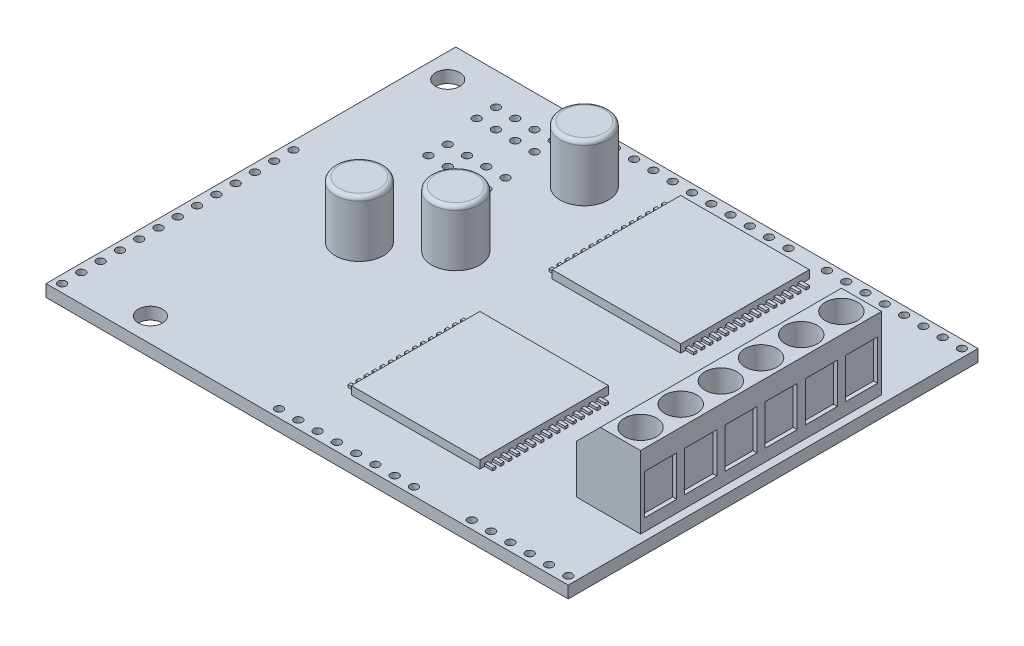
SolidWorks part; units mm, degrees
ref_plane "Спереди" through (0, 0, 0) normal (0, 0, 1) x (1, 0, 0)
ref_plane "Сверху" through (0, 0, 0) normal (0, 1, 0) x (1, 0, 0)
ref_plane "Справа" through (0, 0, 0) normal (1, 0, 0) x (0, 0, -1)
sketch "Эскиз1" plane through (0, 0, 0) normal (0, 1, 0) x (1, 0, 0)
  line L1 (-32.5, 25.5) -> (32.5, 25.5)
  line L2 (-32.5, 25.5) -> (-32.5, -25.5)
  line L3 (-32.5, -25.5) -> (32.5, -25.5)
  line L4 (32.5, 25.5) -> (32.5, -25.5)
  dimension "D1" = 65
  dimension "D2" = 51
  dimension "D3" = 32.5
  dimension "D4" = 25.5
extrude "Бобышка-Вытянуть1" add sketch "Эскиз1" along normal blind 1.5
sketch "Эскиз2" plane through (0, 1.5, 0) normal (0, 1, 0) x (1, 0, 0)
  line L0 (32.5, -25.5) -> (32.5, 25.5) construction
  line L1 (-1.5, 22.5) -> (14.5, 22.5)
  line L2 (-1.5, 22.5) -> (-1.5, 6.5)
  line L3 (-1.5, 6.5) -> (14.5, 6.5)
  line L4 (14.5, 22.5) -> (14.5, 6.5)
  line L5 (32.5, 25.5) -> (-32.5, 25.5) construction
  line L6 (-1.5, -2.5) -> (14.5, -2.5)
  line L7 (-1.5, -2.5) -> (-1.5, -18.5)
  line L8 (-1.5, -18.5) -> (14.5, -18.5)
  line L9 (14.5, -2.5) -> (14.5, -18.5)
  dimension "D1" = 16
  dimension "D2" = 16
  dimension "D3" = 18
  dimension "D4" = 3
  dimension "D5" = 2
extrude "Бобышка-Вытянуть2" add sketch "Эскиз2" along normal blind 1
sketch "Эскиз3" plane through (0, 1.5, 0) normal (0, 1, 0) x (1, 0, 0)
  line L0 (14.5, 6.5) -> (14.5, 22.5) construction
  line L1 (14.5, 21.5) -> (15.5, 21.5)
  line L2 (14.5, 21.5) -> (14.5, 21.1)
  line L3 (14.5, 21.1) -> (15.5, 21.1)
  line L4 (15.5, 21.5) -> (15.5, 21.1)
  line L5 (14.5, 22.5) -> (-1.5, 22.5) construction
  line L6 (14.5, 20.5) -> (15.5, 20.5)
  line L7 (14.5, 20.5) -> (14.5, 20.1)
  line L8 (14.5, 20.1) -> (15.5, 20.1)
  line L9 (15.5, 20.5) -> (15.5, 20.1)
  line L10 (14.5, 19.5) -> (15.5, 19.5)
  line L11 (14.5, 19.5) -> (14.5, 19.1)
  line L12 (14.5, 19.1) -> (15.5, 19.1)
  line L13 (15.5, 19.5) -> (15.5, 19.1)
  line L14 (14.5, 18.5) -> (15.5, 18.5)
  line L15 (14.5, 18.5) -> (14.5, 18.1)
  line L16 (14.5, 18.1) -> (15.5, 18.1)
  line L17 (15.5, 18.5) -> (15.5, 18.1)
  line L18 (14.5, 17.5) -> (15.5, 17.5)
  line L19 (14.5, 17.5) -> (14.5, 17.1)
  line L20 (14.5, 17.1) -> (15.5, 17.1)
  line L21 (15.5, 17.5) -> (15.5, 17.1)
  line L22 (14.5, 16.5) -> (15.5, 16.5)
  line L23 (14.5, 16.5) -> (14.5, 16.1)
  line L24 (14.5, 16.1) -> (15.5, 16.1)
  line L25 (15.5, 16.5) -> (15.5, 16.1)
  line L26 (14.5, 15.5) -> (15.5, 15.5)
  line L27 (14.5, 15.5) -> (14.5, 15.1)
  line L28 (14.5, 15.1) -> (15.5, 15.1)
  line L29 (15.5, 15.5) -> (15.5, 15.1)
  line L30 (14.5, 14.5) -> (15.5, 14.5)
  line L31 (14.5, 14.5) -> (14.5, 14.1)
  line L32 (14.5, 14.1) -> (15.5, 14.1)
  line L33 (15.5, 14.5) -> (15.5, 14.1)
  line L34 (14.5, 13.5) -> (15.5, 13.5)
  line L35 (14.5, 13.5) -> (14.5, 13.1)
  line L36 (14.5, 13.1) -> (15.5, 13.1)
  line L37 (15.5, 13.5) -> (15.5, 13.1)
  line L38 (14.5, 12.5) -> (15.5, 12.5)
  line L39 (14.5, 12.5) -> (14.5, 12.1)
  line L40 (14.5, 12.1) -> (15.5, 12.1)
  line L41 (15.5, 12.5) -> (15.5, 12.1)
  line L42 (14.5, 11.5) -> (15.5, 11.5)
  line L43 (14.5, 11.5) -> (14.5, 11.1)
  line L44 (14.5, 11.1) -> (15.5, 11.1)
  line L45 (15.5, 11.5) -> (15.5, 11.1)
  line L46 (14.5, 10.5) -> (15.5, 10.5)
  line L47 (14.5, 10.5) -> (14.5, 10.1)
  line L48 (14.5, 10.1) -> (15.5, 10.1)
  line L49 (15.5, 10.5) -> (15.5, 10.1)
  line L50 (14.5, 9.5) -> (15.5, 9.5)
  line L51 (14.5, 9.5) -> (14.5, 9.1)
  line L52 (14.5, 9.1) -> (15.5, 9.1)
  line L53 (15.5, 9.5) -> (15.5, 9.1)
  line L54 (14.5, 8.5) -> (15.5, 8.5)
  line L55 (14.5, 8.5) -> (14.5, 8.1)
  line L56 (14.5, 8.1) -> (15.5, 8.1)
  line L57 (15.5, 8.5) -> (15.5, 8.1)
  line L58 (14.5, 7.5) -> (15.5, 7.5)
  line L59 (14.5, 7.5) -> (14.5, 7.1)
  line L60 (14.5, 7.1) -> (15.5, 7.1)
  line L61 (15.5, 7.5) -> (15.5, 7.1)
  line L62 (6.5, 54.7714) -> (6.5, -83.906) construction
  line L63 (-2.5, 7.5) -> (-2.5, 7.1)
  line L64 (-1.5, 7.1) -> (-2.5, 7.1)
  line L65 (-1.5, 7.5) -> (-1.5, 7.1)
  line L66 (-1.5, 7.5) -> (-2.5, 7.5)
  line L67 (-2.5, 8.5) -> (-2.5, 8.1)
  line L68 (-1.5, 8.1) -> (-2.5, 8.1)
  line L69 (-1.5, 8.5) -> (-1.5, 8.1)
  line L70 (-1.5, 8.5) -> (-2.5, 8.5)
  line L71 (-2.5, 9.5) -> (-2.5, 9.1)
  line L72 (-1.5, 9.1) -> (-2.5, 9.1)
  line L73 (-1.5, 9.5) -> (-1.5, 9.1)
  line L74 (-1.5, 9.5) -> (-2.5, 9.5)
  line L75 (-2.5, 10.5) -> (-2.5, 10.1)
  line L76 (-1.5, 10.1) -> (-2.5, 10.1)
  line L77 (-1.5, 10.5) -> (-1.5, 10.1)
  line L78 (-1.5, 10.5) -> (-2.5, 10.5)
  line L79 (-2.5, 11.5) -> (-2.5, 11.1)
  line L80 (-1.5, 11.1) -> (-2.5, 11.1)
  line L81 (-1.5, 11.5) -> (-1.5, 11.1)
  line L82 (-1.5, 11.5) -> (-2.5, 11.5)
  line L83 (-2.5, 12.5) -> (-2.5, 12.1)
  line L84 (-1.5, 12.1) -> (-2.5, 12.1)
  line L85 (-1.5, 12.5) -> (-1.5, 12.1)
  line L86 (-1.5, 12.5) -> (-2.5, 12.5)
  line L87 (-2.5, 13.5) -> (-2.5, 13.1)
  line L88 (-1.5, 13.1) -> (-2.5, 13.1)
  line L89 (-1.5, 13.5) -> (-1.5, 13.1)
  line L90 (-1.5, 13.5) -> (-2.5, 13.5)
  line L91 (-2.5, 14.5) -> (-2.5, 14.1)
  line L92 (-1.5, 14.1) -> (-2.5, 14.1)
  line L93 (-1.5, 14.5) -> (-1.5, 14.1)
  line L94 (-1.5, 14.5) -> (-2.5, 14.5)
  line L95 (-2.5, 15.5) -> (-2.5, 15.1)
  line L96 (-1.5, 15.1) -> (-2.5, 15.1)
  line L97 (-1.5, 15.5) -> (-1.5, 15.1)
  line L98 (-1.5, 15.5) -> (-2.5, 15.5)
  line L99 (-2.5, 16.5) -> (-2.5, 16.1)
  line L100 (-1.5, 16.1) -> (-2.5, 16.1)
  line L101 (-1.5, 16.5) -> (-1.5, 16.1)
  line L102 (-1.5, 16.5) -> (-2.5, 16.5)
  line L103 (-2.5, 17.5) -> (-2.5, 17.1)
  line L104 (-1.5, 17.1) -> (-2.5, 17.1)
  line L105 (-1.5, 17.5) -> (-1.5, 17.1)
  line L106 (-1.5, 17.5) -> (-2.5, 17.5)
  line L107 (-2.5, 18.5) -> (-2.5, 18.1)
  line L108 (-1.5, 18.1) -> (-2.5, 18.1)
  line L109 (-1.5, 18.5) -> (-1.5, 18.1)
  line L110 (-1.5, 18.5) -> (-2.5, 18.5)
  line L111 (-2.5, 19.5) -> (-2.5, 19.1)
  line L112 (-1.5, 19.1) -> (-2.5, 19.1)
  line L113 (-1.5, 19.5) -> (-1.5, 19.1)
  line L114 (-1.5, 19.5) -> (-2.5, 19.5)
  line L115 (-2.5, 20.5) -> (-2.5, 20.1)
  line L116 (-1.5, 20.1) -> (-2.5, 20.1)
  line L117 (-1.5, 20.5) -> (-1.5, 20.1)
  line L118 (-1.5, 20.5) -> (-2.5, 20.5)
  line L119 (-2.5, 21.5) -> (-2.5, 21.1)
  line L120 (-1.5, 21.1) -> (-2.5, 21.1)
  line L121 (-1.5, 21.5) -> (-1.5, 21.1)
  line L122 (-1.5, 21.5) -> (-2.5, 21.5)
  line L123 (14.5, -3.5) -> (15.5, -3.5)
  line L124 (14.5, -3.5) -> (14.5, -3.9)
  line L125 (14.5, -3.9) -> (15.5, -3.9)
  line L126 (15.5, -3.5) -> (15.5, -3.9)
  line L127 (14.5, -4.5) -> (15.5, -4.5)
  line L128 (14.5, -4.5) -> (14.5, -4.9)
  line L129 (14.5, -4.9) -> (15.5, -4.9)
  line L130 (15.5, -4.5) -> (15.5, -4.9)
  line L131 (14.5, -5.5) -> (15.5, -5.5)
  line L132 (14.5, -5.5) -> (14.5, -5.9)
  line L133 (14.5, -5.9) -> (15.5, -5.9)
  line L134 (15.5, -5.5) -> (15.5, -5.9)
  line L135 (14.5, -6.5) -> (15.5, -6.5)
  line L136 (14.5, -6.5) -> (14.5, -6.9)
  line L137 (14.5, -6.9) -> (15.5, -6.9)
  line L138 (15.5, -6.5) -> (15.5, -6.9)
  line L139 (14.5, -7.5) -> (15.5, -7.5)
  line L140 (14.5, -7.5) -> (14.5, -7.9)
  line L141 (14.5, -7.9) -> (15.5, -7.9)
  line L142 (15.5, -7.5) -> (15.5, -7.9)
  line L143 (14.5, -8.5) -> (15.5, -8.5)
  line L144 (14.5, -8.5) -> (14.5, -8.9)
  line L145 (14.5, -8.9) -> (15.5, -8.9)
  line L146 (15.5, -8.5) -> (15.5, -8.9)
  line L147 (14.5, -9.5) -> (15.5, -9.5)
  line L148 (14.5, -9.5) -> (14.5, -9.9)
  line L149 (14.5, -9.9) -> (15.5, -9.9)
  line L150 (15.5, -9.5) -> (15.5, -9.9)
  line L151 (14.5, -10.5) -> (15.5, -10.5)
  line L152 (14.5, -10.5) -> (14.5, -10.9)
  line L153 (14.5, -10.9) -> (15.5, -10.9)
  line L154 (15.5, -10.5) -> (15.5, -10.9)
  line L155 (14.5, -11.5) -> (15.5, -11.5)
  line L156 (14.5, -11.5) -> (14.5, -11.9)
  line L157 (14.5, -11.9) -> (15.5, -11.9)
  line L158 (15.5, -11.5) -> (15.5, -11.9)
  line L159 (14.5, -12.5) -> (15.5, -12.5)
  line L160 (14.5, -12.5) -> (14.5, -12.9)
  line L161 (14.5, -12.9) -> (15.5, -12.9)
  line L162 (15.5, -12.5) -> (15.5, -12.9)
  line L163 (14.5, -13.5) -> (15.5, -13.5)
  line L164 (14.5, -13.5) -> (14.5, -13.9)
  line L165 (14.5, -13.9) -> (15.5, -13.9)
  line L166 (15.5, -13.5) -> (15.5, -13.9)
  line L167 (14.5, -14.5) -> (15.5, -14.5)
  line L168 (14.5, -14.5) -> (14.5, -14.9)
  line L169 (14.5, -14.9) -> (15.5, -14.9)
  line L170 (15.5, -14.5) -> (15.5, -14.9)
  line L171 (14.5, -15.5) -> (15.5, -15.5)
  line L172 (14.5, -15.5) -> (14.5, -15.9)
  line L173 (14.5, -15.9) -> (15.5, -15.9)
  line L174 (15.5, -15.5) -> (15.5, -15.9)
  line L175 (14.5, -16.5) -> (15.5, -16.5)
  line L176 (14.5, -16.5) -> (14.5, -16.9)
  line L177 (14.5, -16.9) -> (15.5, -16.9)
  line L178 (15.5, -16.5) -> (15.5, -16.9)
  line L179 (14.5, -17.5) -> (15.5, -17.5)
  line L180 (14.5, -17.5) -> (14.5, -17.9)
  line L181 (14.5, -17.9) -> (15.5, -17.9)
  line L182 (15.5, -17.5) -> (15.5, -17.9)
  line L183 (-2.5, -17.5) -> (-2.5, -17.9)
  line L184 (-1.5, -17.9) -> (-2.5, -17.9)
  line L185 (-1.5, -17.5) -> (-1.5, -17.9)
  line L186 (-1.5, -17.5) -> (-2.5, -17.5)
  line L187 (-2.5, -16.5) -> (-2.5, -16.9)
  line L188 (-1.5, -16.9) -> (-2.5, -16.9)
  line L189 (-1.5, -16.5) -> (-1.5, -16.9)
  line L190 (-1.5, -16.5) -> (-2.5, -16.5)
  line L191 (-2.5, -15.5) -> (-2.5, -15.9)
  line L192 (-1.5, -15.9) -> (-2.5, -15.9)
  line L193 (-1.5, -15.5) -> (-1.5, -15.9)
  line L194 (-1.5, -15.5) -> (-2.5, -15.5)
  line L195 (-2.5, -14.5) -> (-2.5, -14.9)
  line L196 (-1.5, -14.9) -> (-2.5, -14.9)
  line L197 (-1.5, -14.5) -> (-1.5, -14.9)
  line L198 (-1.5, -14.5) -> (-2.5, -14.5)
  line L199 (-2.5, -13.5) -> (-2.5, -13.9)
  line L200 (-1.5, -13.9) -> (-2.5, -13.9)
  line L201 (-1.5, -13.5) -> (-1.5, -13.9)
  line L202 (-1.5, -13.5) -> (-2.5, -13.5)
  line L203 (-2.5, -12.5) -> (-2.5, -12.9)
  line L204 (-1.5, -12.9) -> (-2.5, -12.9)
  line L205 (-1.5, -12.5) -> (-1.5, -12.9)
  line L206 (-1.5, -12.5) -> (-2.5, -12.5)
  line L207 (-2.5, -11.5) -> (-2.5, -11.9)
  line L208 (-1.5, -11.9) -> (-2.5, -11.9)
  line L209 (-1.5, -11.5) -> (-1.5, -11.9)
  line L210 (-1.5, -11.5) -> (-2.5, -11.5)
  line L211 (-2.5, -10.5) -> (-2.5, -10.9)
  line L212 (-1.5, -10.9) -> (-2.5, -10.9)
  line L213 (-1.5, -10.5) -> (-1.5, -10.9)
  line L214 (-1.5, -10.5) -> (-2.5, -10.5)
  line L215 (-2.5, -9.5) -> (-2.5, -9.9)
  line L216 (-1.5, -9.9) -> (-2.5, -9.9)
  line L217 (-1.5, -9.5) -> (-1.5, -9.9)
  line L218 (-1.5, -9.5) -> (-2.5, -9.5)
  line L219 (-2.5, -8.5) -> (-2.5, -8.9)
  line L220 (-1.5, -8.9) -> (-2.5, -8.9)
  line L221 (-1.5, -8.5) -> (-1.5, -8.9)
  line L222 (-1.5, -8.5) -> (-2.5, -8.5)
  line L223 (-2.5, -7.5) -> (-2.5, -7.9)
  line L224 (-1.5, -7.9) -> (-2.5, -7.9)
  line L225 (-1.5, -7.5) -> (-1.5, -7.9)
  line L226 (-1.5, -7.5) -> (-2.5, -7.5)
  line L227 (-2.5, -6.5) -> (-2.5, -6.9)
  line L228 (-1.5, -6.9) -> (-2.5, -6.9)
  line L229 (-1.5, -6.5) -> (-1.5, -6.9)
  line L230 (-1.5, -6.5) -> (-2.5, -6.5)
  line L231 (-2.5, -5.5) -> (-2.5, -5.9)
  line L232 (-1.5, -5.9) -> (-2.5, -5.9)
  line L233 (-1.5, -5.5) -> (-1.5, -5.9)
  line L234 (-1.5, -5.5) -> (-2.5, -5.5)
  line L235 (-2.5, -4.5) -> (-2.5, -4.9)
  line L236 (-1.5, -4.9) -> (-2.5, -4.9)
  line L237 (-1.5, -4.5) -> (-1.5, -4.9)
  line L238 (-1.5, -4.5) -> (-2.5, -4.5)
  line L239 (-2.5, -3.5) -> (-2.5, -3.9)
  line L240 (-1.5, -3.9) -> (-2.5, -3.9)
  line L241 (-1.5, -3.5) -> (-1.5, -3.9)
  line L242 (-1.5, -3.5) -> (-2.5, -3.5)
  dimension "D1" = 0.4
  dimension "D2" = 1
  dimension "D3" = 1
  dimension "D5" = 8
  dimension "D6" = 8
  dimension "D4" = 15
  dimension "D7" = 2
extrude "Бобышка-Вытянуть3" add sketch "Эскиз3" along normal blind 0.3
sketch "Эскиз4" plane through (0, 1.5, 0) normal (0, 1, 0) x (1, 0, 0)
  line L0 (32.5, -25.5) -> (32.5, 25.5) construction
  line L1 (-32.5, -25.5) -> (32.5, -25.5) construction
  line L2 (32.5, 25.5) -> (-32.5, 25.5) construction
  line L3 (-32.5, 25.5) -> (-32.5, -25.5) construction
  circle A0 centre (31.5, -24.5) radius 0.5
  circle A1 centre (29.1, -24.5) radius 0.5
  circle A2 centre (26.7, -24.5) radius 0.5
  circle A3 centre (24.3, -24.5) radius 0.5
  circle A4 centre (21.9, -24.5) radius 0.5
  circle A5 centre (19.5, -24.5) radius 0.5
  circle A6 centre (31.5, 24.5) radius 0.5
  circle A7 centre (29.1, 24.5) radius 0.5
  circle A8 centre (12.3, -24.5) radius 0.5
  circle A9 centre (9.9, -24.5) radius 0.5
  circle A10 centre (7.5, -24.5) radius 0.5
  circle A11 centre (5.1, -24.5) radius 0.5
  circle A12 centre (2.7, -24.5) radius 0.5
  circle A13 centre (0.3, -24.5) radius 0.5
  circle A14 centre (-2.1, -24.5) radius 0.5
  circle A15 centre (-4.5, -24.5) radius 0.5
  circle A16 centre (17.1, -24.5) radius 0.5 [skipped]
  circle A17 centre (14.7, -24.5) radius 0.5 [skipped]
  circle A18 centre (26.7, 24.5) radius 0.5
  circle A19 centre (24.3, 24.5) radius 0.5
  circle A20 centre (21.9, 24.5) radius 0.5
  circle A21 centre (19.5, 24.5) radius 0.5
  circle A22 centre (17.1, 24.5) radius 0.5
  circle A23 centre (14.7, 24.5) radius 0.5
  circle A24 centre (-31.5, -24.5) radius 0.5
  circle A25 centre (9.9, 24.5) radius 0.5
  circle A26 centre (7.5, 24.5) radius 0.5
  circle A27 centre (5.1, 24.5) radius 0.5
  circle A28 centre (2.7, 24.5) radius 0.5
  circle A29 centre (0.3, 24.5) radius 0.5
  circle A30 centre (-2.1, 24.5) radius 0.5
  circle A31 centre (-4.5, 24.5) radius 0.5
  circle A32 centre (-6.9, 24.5) radius 0.5
  circle A33 centre (-9.3, 24.5) radius 0.5
  circle A34 centre (-11.7, 24.5) radius 0.5
  circle A35 centre (12.3, 24.5) radius 0.5 [skipped]
  circle A36 centre (-31.5, -22.1) radius 0.5
  circle A37 centre (-31.5, -19.7) radius 0.5
  circle A38 centre (-31.5, -17.3) radius 0.5
  circle A39 centre (-31.5, -14.9) radius 0.5
  circle A40 centre (-31.5, -12.5) radius 0.5
  circle A41 centre (-31.5, -10.1) radius 0.5
  circle A42 centre (-31.5, -7.7) radius 0.5
  circle A43 centre (-31.5, -5.3) radius 0.5
  circle A44 centre (-31.5, -2.9) radius 0.5
  circle A45 centre (-31.5, -0.5) radius 0.5
  circle A46 centre (-31.5, 1.9) radius 0.5
  circle A47 centre (-31.5, 4.3) radius 0.5
  circle A48 centre (-29.5, 21.5) radius 1.5
  circle A49 centre (-22.5, -22.5) radius 1.5
  circle A50 centre (-23.5, 21.5) radius 0.5
  circle A51 centre (-21.1, 21.5) radius 0.5
  circle A52 centre (-18.7, 21.5) radius 0.5
  circle A53 centre (-16.3, 21.5) radius 0.5
  circle A54 centre (-21.1, 19.1) radius 0.5
  circle A55 centre (-18.7, 19.1) radius 0.5
  circle A56 centre (-16.3, 19.1) radius 0.5
  circle A57 centre (-23.5, 19.1) radius 0.5
  circle A58 centre (-22.5, 14.5) radius 0.5
  circle A59 centre (-20.1, 14.5) radius 0.5
  circle A60 centre (-17.7, 14.5) radius 0.5
  circle A61 centre (-15.3, 14.5) radius 0.5
  circle A62 centre (-20.1, 12.1) radius 0.5
  circle A63 centre (-17.7, 12.1) radius 0.5
  circle A64 centre (-15.3, 12.1) radius 0.5
  circle A65 centre (-22.5, 12.1) radius 0.5
  dimension "D1" = 1
  dimension "D5" = 1
  dimension "D9" = 1
  dimension "D12" = 13
  dimension "D13" = 3
  dimension "D16" = 3
  dimension "D19" = 1
  dimension "D2" = 1
  dimension "D3" = 1
  dimension "D6" = 1
  dimension "D7" = 1
  dimension "D10" = 1
  dimension "D11" = 1
  dimension "D14" = 4
  dimension "D15" = 3
  dimension "D17" = 3
  dimension "D18" = 10
  dimension "D20" = 4
  dimension "D21" = 9
  dimension "D24" = 10
  dimension "D25" = 11
  dimension "D4" = 16
  dimension "D8" = 19
  dimension "D22" = 4
  dimension "D23" = 2
  dimension "D26" = 4
  dimension "D27" = 2
extrude "Вырез-Вытянуть1" cut sketch "Эскиз4" against normal blind 2
sketch "Эскиз5" plane through (0, 1.5, 0) normal (0, 1, 0) x (1, 0, 0)
  line L1 (23.5, 14.5) -> (31.5, 14.5)
  line L2 (23.5, 14.5) -> (23.5, -15.5)
  line L3 (23.5, -15.5) -> (31.5, -15.5)
  line L4 (31.5, 14.5) -> (31.5, -15.5)
  point P6 (39.2871, 20.1959)
  dimension "D1" = 30
  dimension "D2" = 8
  dimension "D3" = 11
  dimension "D4" = 1
extrude "Бобышка-Вытянуть4" add sketch "Эскиз5" along normal blind 9
chamfer "Фаска1" distance 3 angle 45 1 edges at (23.5, 10.5, 0.5)
sketch "Эскиз6" plane through (0, 10.5, 0) normal (0, 1, 0) x (1, 0, 0)
  line L0 (31.5, 14.5) -> (23.5, 14.5) construction
  line L1 (31.5, -15.5) -> (31.5, 14.5) construction
  circle A0 centre (28.9993, 12) radius 2
  circle A1 centre (28.9993, 7) radius 2
  circle A2 centre (28.9993, 2) radius 2
  circle A3 centre (28.9993, -3) radius 2
  circle A4 centre (28.9993, -8) radius 2
  circle A5 centre (28.9993, -13) radius 2
  dimension "D1" = 4
  dimension "D2" = 2.5
  dimension "D3" = 2.5007
  dimension "D4" = 6
extrude "Вырез-Вытянуть2" cut sketch "Эскиз6" against normal blind 4
sketch "Эскиз7" plane through (31.5, 0, 0) normal (1, 0, 0) x (0, 0, -1)
  line L0 (14.5, 10.5) -> (14.5, 1.5) construction
  line L1 (14, 8) -> (10, 8)
  line L2 (14, 8) -> (14, 3)
  line L3 (14, 3) -> (10, 3)
  line L4 (10, 8) -> (10, 3)
  line L5 (-15.5, 1.5) -> (14.5, 1.5) construction
  line L6 (9, 8) -> (5, 8)
  line L7 (9, 8) -> (9, 3)
  line L8 (9, 3) -> (5, 3)
  line L9 (5, 8) -> (5, 3)
  line L10 (4, 8) -> (0, 8)
  line L11 (4, 8) -> (4, 3)
  line L12 (4, 3) -> (0, 3)
  line L13 (0, 8) -> (0, 3)
  line L14 (-1, 8) -> (-5, 8)
  line L15 (-1, 8) -> (-1, 3)
  line L16 (-1, 3) -> (-5, 3)
  line L17 (-5, 8) -> (-5, 3)
  line L18 (-6, 8) -> (-10, 8)
  line L19 (-6, 8) -> (-6, 3)
  line L20 (-6, 3) -> (-10, 3)
  line L21 (-10, 8) -> (-10, 3)
  line L22 (-11, 8) -> (-15, 8)
  line L23 (-11, 8) -> (-11, 3)
  line L24 (-11, 3) -> (-15, 3)
  line L25 (-15, 8) -> (-15, 3)
  dimension "D1" = 4
  dimension "D2" = 0.5
  dimension "D3" = 1.5
  dimension "D4" = 5
  dimension "D5" = 6
extrude "Вырез-Вытянуть3" cut sketch "Эскиз7" against normal blind 0.5
sketch "Эскиз8" plane through (8, -8, 0) normal (-0.7071, 0.7071, 0) x (0, 0, 1)
  line L0 (-14.5, 21.9203) -> (-14.5, 26.163) construction
  line L1 (15.5, 21.9203) -> (-14.5, 21.9203) construction
  circle A0 centre (-12, 23.9203) radius 0.5
  circle A1 centre (-7, 23.9203) radius 0.5
  circle A2 centre (-2, 23.9203) radius 0.5
  circle A3 centre (3, 23.9203) radius 0.5
  circle A4 centre (8, 23.9203) radius 0.5
  circle A5 centre (13, 23.9203) radius 0.5
  point P2 (-14.5, 24.0416)
  dimension "D1" = 1
  dimension "D2" = 2.5
  dimension "D3" = 2
  dimension "D4" = 6
extrude "Вырез-Вытянуть4" cut sketch "Эскиз8" against normal blind 0.2
sketch "Эскиз9" plane through (0, 1.5, 0) normal (0, 1, 0) x (1, 0, 0)
  line L0 (-32.5, 25.5) -> (-32.5, -25.5) construction
  line L1 (32.5, 25.5) -> (-32.5, 25.5) construction
  circle A0 centre (-9.5, 18.5) radius 3
  circle A1 centre (-17.5, -1.5) radius 3
  circle A2 centre (-10.5, 3.5) radius 3
  dimension "D1" = 6
  dimension "D2" = 23
  dimension "D3" = 7
  dimension "D4" = 22
  dimension "D5" = 22
  dimension "D6" = 15
  dimension "D7" = 27
extrude "Бобышка-Вытянуть5" add sketch "Эскиз9" along normal blind 7
fillet "Скругление1" radius 0.5 3 edges at (-17.5, 8.5, 4.5) (-10.5, 8.5, -0.5) (-9.5, 8.5, -15.5)
